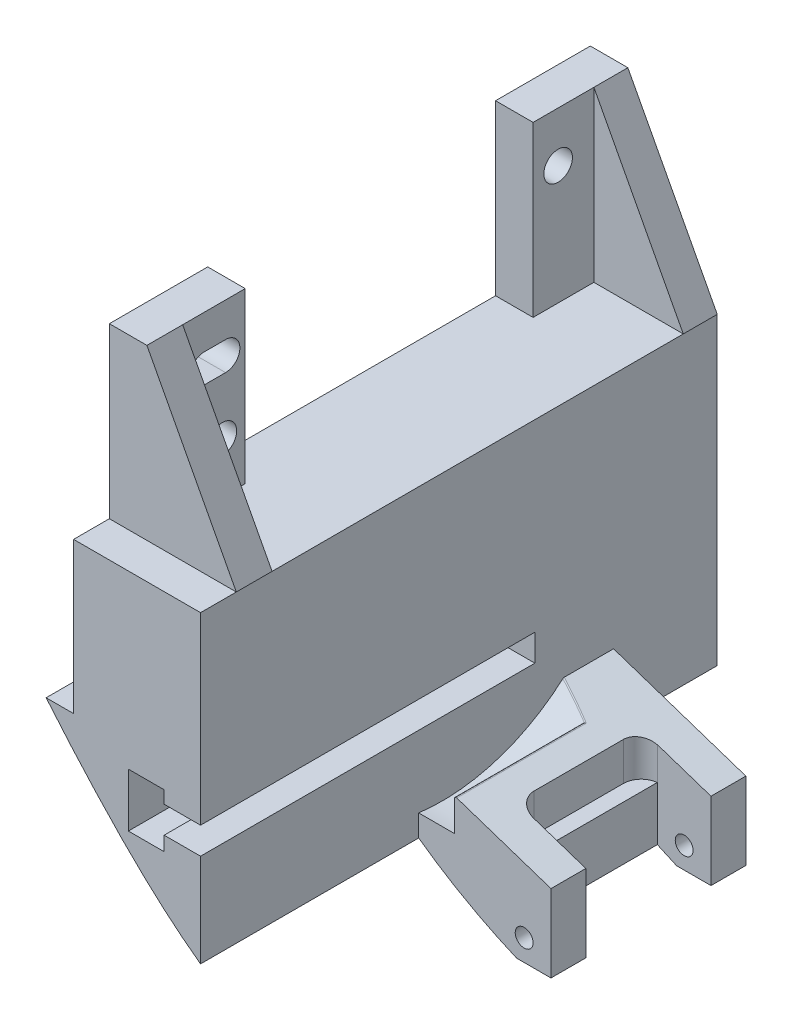
SolidWorks part; units mm, degrees
ref_plane "Front Plane" through (0, 0, 0) normal (0, 0, 1) x (1, 0, 0)
ref_plane "Top Plane" through (0, 0, 0) normal (0, 1, 0) x (1, 0, 0)
ref_plane "Right Plane" through (0, 0, 0) normal (1, 0, 0) x (0, 0, -1)
sketch "Sketch1" plane through (0, 0, 0) normal (0, 0, 1) x (1, 0, 0)
  line L0 (0, 0) -> (-802.64, 0) construction
  line L1 (-748.665, 44.1696) -> (-748.665, -74.6704)
  line L2 (-748.665, -30.2204) -> (-761.365, -6.2242)
  line L3 (-761.365, -6.2242) -> (-766.699, -6.2242)
  line L4 (-766.699, -6.2242) -> (-766.699, -51.6582)
  line L5 (-766.699, -51.6582) -> (-771.8965, -51.6582)
  line L6 (-748.665, -64.0024) -> (-729.869, -70.266)
  line L7 (-729.869, -70.266) -> (-729.869, -81.2664)
  line L8 (-729.869, -81.2664) -> (-737.2182, -81.2664)
  spline S0 degree 3 poles (0, 0) (-1.0237, 0.2656) (-4.9202, 1.2766) (-12.9449, 4.1039) (-25.4013, 8.4868) (-42.0665, 13.5118) (-62.8454, 18.7065) (-87.4855, 24.5937) (-115.6566, 31.0073) (-146.8786, 37.8673) (-180.6724, 44.9921) (-216.5548, 52.1802) (-254.0529, 59.2076) (-292.7123, 65.838) (-332.0988, 71.84) (-371.8025, 76.9957) (-411.4364, 81.107) (-450.6369, 83.9911) (-489.077, 85.531) (-526.5224, 85.442) (-562.7196, 83.818) (-597.4628, 80.7564) (-630.4517, 76.3148) (-661.4214, 70.7397) (-690.0483, 64.1559) (-716.031, 56.6856) (-739.0944, 48.4855) (-758.9977, 39.6811) (-775.5284, 30.474) (-788.4955, 21.0643) (-796.9293, 12.5202) (-800.9086, 6.2407) (-802.1089, 3.1045) (-802.4813, 1.6746) (-802.6246, 0.7789) (-802.6361, 0.1966) (-802.64, 0) knots 0 0 0 0 0.003802 0.014472 0.030564 0.051299 0.077028 0.107574 0.142399 0.180921 0.222525 0.266591 0.312515 0.35971 0.407632 0.455773 0.503669 0.550901 0.597096 0.641976 0.685512 0.727353 0.767354 0.805169 0.840471 0.872937 0.902335 0.928425 0.951113 0.970253 0.985871 0.993982 0.996753 0.997907 0.999293 1 1 1 1
  spline S1 degree 3 poles (-802.64, 0) (-802.6044, -0.5181) (-802.5144, -1.8305) (-801.9167, -4.3742) (-799.7349, -10.5214) (-793.9295, -20.2585) (-785.3431, -33.6018) (-775.1978, -47.9717) (-763.534, -61.6115) (-750.6842, -74.1505) (-734.4646, -83.2964) (-715.0378, -88.7141) (-692.4973, -92.3639) (-666.7697, -93.8876) (-638.0856, -93.4064) (-606.5863, -90.9175) (-572.4417, -86.5307) (-535.8367, -80.4015) (-496.9928, -72.7658) (-456.1802, -63.9255) (-413.7333, -54.2411) (-370.0617, -44.1324) (-325.6653, -34.0384) (-281.1348, -24.4182) (-237.1588, -15.6974) (-194.5105, -8.2549) (-154.0343, -2.3799) (-116.6158, 1.7567) (-83.1483, 4.1076) (-54.5227, 4.8332) (-31.6235, 4.0558) (-15.153, 2.4109) (-5.3471, 1.0064) (-1.061, 0.1997) (0, 0) knots 0 0 0 0 0.001821 0.004613 0.009135 0.024676 0.044153 0.064937 0.086321 0.107138 0.1276 0.150893 0.177565 0.207668 0.241222 0.278203 0.318526 0.362031 0.408465 0.457479 0.508614 0.561296 0.614835 0.668438 0.721214 0.772202 0.820393 0.864766 0.904324 0.938132 0.965242 0.98469 0.99621 1 1 1 1
  spline S2 degree 1 poles (-801.6423, 0.0685) (0.185, 0.9827) knots 0 0 1 1 construction
  spline S3 degree 3 poles (-801.6423, 0.0685) (-801.6237, -0.2032) (-801.5856, -0.7575) (-801.4767, -1.7745) (-801.2061, -3.0474) (-800.7523, -4.6051) (-799.6861, -7.6655) (-797.5851, -12.1121) (-794.186, -17.8214) (-789.4599, -25.3717) (-783.3821, -34.6366) (-775.6705, -45.5008) (-768.683, -54.0786) (-762.7345, -60.658) (-758.1103, -65.4458) (-753.2531, -69.943) (-746.3395, -75.3517) (-736.7143, -80.8312) (-724.2384, -85.2314) (-711.2485, -88.2163) (-698.134, -90.3911) (-684.9012, -91.7723) (-671.602, -92.498) (-653.8378, -92.7605) (-631.6341, -91.9649) (-605.061, -89.6531) (-578.5923, -86.3156) (-552.2299, -82.1851) (-517.21, -75.8642) (-473.6438, -66.8228) (-421.5579, -55.0352) (-369.5251, -42.9695) (-317.4245, -31.1532) (-265.1531, -20.0658) (-212.6314, -10.1632) (-159.8037, -1.9572) (-115.5013, 2.95) (-79.9088, 5.1973) (-53.1547, 5.839) (-30.8229, 5.0205) (-15.2792, 3.3879) (-6.4157, 2.1851) (-2.0125, 1.3963) (0.185, 0.9827) knots 0 0 0 0 0.000977 0.001953 0.003906 0.005859 0.007812 0.015625 0.023437 0.03125 0.046875 0.0625 0.078125 0.085937 0.09375 0.101562 0.109375 0.125 0.140625 0.15625 0.171875 0.1875 0.203125 0.21875 0.25 0.28125 0.3125 0.34375 0.375 0.4375 0.5 0.5625 0.625 0.6875 0.75 0.8125 0.875 0.90625 0.9375 0.96875 0.984375 0.992187 1 1 1 1
  point P6 (-748.665, -30.2204)
  dimension "D2" = 802.64
  dimension "D3" = 44.45
  dimension "D4" = 18.034
  dimension "D5" = 5.334
  dimension "D6" = 117.89
  dimension "D7" = 1
  dimension "D8" = 108.43
  dimension "D9" = 18.796
  dimension "D10" = 10.668
  dimension "D11" = 53.975
extrude "Boss-Extrude1" add sketch "Sketch1" along normal blind 73.406 contours L5 S1 L1 L2 L3 L4 | L1 S1 L8 L7 L6
sketch "Sketch2" plane through (-748.665, 0, 0) normal (1, 0, 0) x (0, 0, -1)
  line L0 (-73.406, -30.2204) -> (0, -30.2204) construction
  line L1 (-73.406, -6.2242) -> (-68.326, -6.2242)
  line L2 (-73.406, -6.2242) -> (-73.406, -30.2204)
  line L3 (-73.406, -30.2204) -> (-68.326, -30.2204)
  line L4 (-68.326, -6.2242) -> (-68.326, -30.2204)
  line L5 (-73.406, -6.2242) -> (0, -6.2242) construction
  line L6 (-54.356, -6.2242) -> (-13.462, -6.2242)
  line L7 (-54.356, -6.2242) -> (-54.356, -30.2204)
  line L8 (-54.356, -30.2204) -> (-13.462, -30.2204)
  line L9 (-13.462, -6.2242) -> (-13.462, -30.2204)
  dimension "D1" = 5.08
  dimension "D2" = 13.97
  dimension "D3" = 40.894
extrude "Cut-Extrude1" cut sketch "Sketch2" against normal through all
sketch "Sketch3" plane through (-748.665, 0, 0) normal (1, 0, 0) x (0, 0, -1)
  line L0 (-68.326, -6.2242) -> (-54.356, -6.2242) construction
  line L1 (-63.246, -6.2242) -> (-4.826, -6.2242)
  line L2 (-63.246, -6.2242) -> (-63.246, -30.2204)
  line L3 (-63.246, -30.2204) -> (-4.826, -30.2204)
  line L4 (-4.826, -6.2242) -> (-4.826, -30.2204)
  line L5 (-13.462, -30.2204) -> (0, -30.2204) construction
  line L6 (-68.326, -6.2242) -> (-68.326, -30.2204) construction
  point P10 (-63.246, -18.2223)
  dimension "D1" = 5.08
  dimension "D2" = 58.42
extrude "Cut-Extrude2" cut sketch "Sketch3" against normal up to vertex (12.7 mm away) up to point (-761.365, -6.2242, 13.462)
sketch "Sketch4" plane through (-761.365, 0, 0) normal (1, 0, 0) x (0, 0, -1)
  line L0 (-60.198, -13.1338) -> (-57.15, -13.1338) construction
  line L3 (-10.668, -33.8067) -> (-7.62, -33.8067) construction
  line L6 (-60.198, -11.1018) -> (-57.15, -11.1018)
  line L7 (-63.246, -30.2204) -> (-54.356, -30.2204) construction
  line L8 (-4.826, -30.2204) -> (-4.826, -6.2242) construction
  line L9 (-13.462, -6.2242) -> (-4.826, -6.2242) construction
  line L10 (-4.826, -6.2242) -> (-4.826, -30.2204) construction
  line L12 (-60.198, -15.1658) -> (-57.15, -15.1658)
  line L13 (-54.356, -6.2242) -> (-63.246, -6.2242) construction
  line L14 (-63.246, -30.2204) -> (-63.246, -6.2242) construction
  line L15 (-10.668, -31.7747) -> (-7.62, -31.7747)
  line L16 (-10.668, -35.8387) -> (-7.62, -35.8387)
  circle A0 centre (-57.6105, -23.1084) radius 2.032
  circle A1 centre (-9.906, -13.3362) radius 2.032
  arc A6 (-60.198, -11.1018) -> (-60.198, -15.1658) centre (-60.198, -13.1338) ccw
  arc A7 (-57.15, -15.1658) -> (-57.15, -11.1018) centre (-57.15, -13.1338) ccw
  arc A8 (-10.668, -31.7747) -> (-10.668, -35.8387) centre (-10.668, -33.8067) ccw
  arc A9 (-7.62, -35.8387) -> (-7.62, -31.7747) centre (-7.62, -33.8067) ccw
  point P6 (-58.674, -13.1338)
  point P13 (-9.144, -33.8067)
  dimension "D3" = 4.064
  dimension "D4" = 4.064
  dimension "D5" = 5.08
  dimension "D6" = 7.112
  dimension "D8" = 4.064
  dimension "D14" = 4.318
  dimension "D10" = 2.032
  dimension "D2" = 7.112
  dimension "D7" = 3.048
  dimension "D9" = 3.048
  dimension "D11" = 6.9096
  dimension "D12" = 4.572
  dimension "D13" = 5.6355
extrude "Cut-Extrude3" cut sketch "Sketch4" against normal through all
sketch "Sketch5" plane through (-729.869, 0, 0) normal (1, 0, 0) x (0, 0, -1)
  line L0 (-73.406, -81.2664) -> (0, -81.2664) construction
  line L1 (-73.406, -64.0024) -> (-42.418, -64.0024)
  line L2 (-73.406, -64.0024) -> (-73.406, -81.2664)
  line L3 (-73.406, -81.2664) -> (-42.418, -81.2664)
  line L4 (-42.418, -64.0024) -> (-42.418, -81.2664)
  line L5 (-73.406, -64.0024) -> (0, -64.0024) construction
  line L6 (-14.732, -64.0024) -> (0, -64.0024)
  line L7 (-14.732, -64.0024) -> (-14.732, -81.2664)
  line L8 (-14.732, -81.2664) -> (0, -81.2664)
  line L9 (0, -64.0024) -> (0, -81.2664)
  dimension "D1" = 30.988
  dimension "D2" = 14.732
extrude "Cut-Extrude4" cut sketch "Sketch5" against normal up to vertex (18.796 mm away)
sketch "Sketch6" plane through (0, 0, 73.406) normal (0, 0, 1) x (1, 0, 0)
  line L10 (-748.665, 44.1696) -> (-748.665, -74.6704) construction
  line L11 (-748.665, -56.3744) -> (-748.665, -60.1844)
  line L12 (-748.665, -60.1844) -> (-753.8364, -60.1844)
  line L13 (-753.8364, -60.1844) -> (-753.8364, -62.2164)
  line L14 (-753.8364, -62.2164) -> (-758.9164, -62.2164)
  line L15 (-758.9164, -62.2164) -> (-758.9164, -54.5964)
  line L16 (-758.9164, -54.5964) -> (-753.8364, -54.5964)
  line L17 (-753.8364, -54.5964) -> (-753.8364, -56.3744)
  line L18 (-753.8364, -56.3744) -> (-748.665, -56.3744)
  line L19 (-729.869, -81.2664) -> (-737.2182, -81.2664) construction
  dimension "D7" = 7.62
  dimension "D8" = 5.08
  dimension "D9" = 5.1714
  dimension "D10" = 3.81
  dimension "D11" = 2.032
  dimension "D12" = 19.05
extrude "Cut-Extrude5" cut sketch "Sketch6" against normal blind 47.498
sketch "Sketch7" plane through (0, -81.2664, 0) normal (0, -1, 0) x (1, 0, 0)
  line L0 (-729.869, 42.418) -> (-729.869, 14.732) construction
  line L1 (-729.869, 37.465) -> (-737.489, 37.465)
  line L2 (-729.869, 37.465) -> (-729.869, 19.685)
  line L3 (-729.869, 19.685) -> (-737.489, 19.685)
  line L4 (-737.489, 37.465) -> (-737.489, 19.685)
  line L5 (-734.751, 42.418) -> (-729.869, 42.418) construction
  line L6 (-734.751, 14.732) -> (-729.869, 14.732) construction
  dimension "D1" = 7.62
  dimension "D2" = 17.78
  dimension "D3" = 4.953
  dimension "D4" = 4.953
extrude "Cut-Extrude6" cut sketch "Sketch7" against normal blind 22.098
sketch "Sketch8" plane through (0, -30.2204, 0) normal (0, 1, 0) x (1, 0, 0)
  line L1 (-729.869, -37.465) -> (-737.235, -37.465)
  line L2 (-729.869, -37.465) -> (-729.869, -19.685)
  line L3 (-729.869, -19.685) -> (-737.235, -19.685)
  line L4 (-739.775, -34.925) -> (-739.775, -22.225)
  arc A0 (-737.235, -19.685) -> (-739.775, -22.225) centre (-737.235, -22.225) ccw
  arc A1 (-739.775, -34.925) -> (-737.235, -37.465) centre (-737.235, -34.925) ccw
  dimension "D3" = 2.54
  dimension "D1" = 17.78
  dimension "D2" = 9.906
extrude "Cut-Extrude7" cut sketch "Sketch8" against normal blind 42.164
sketch "Sketch9" plane through (0, 0, 42.418) normal (0, 0, 1) x (1, 0, 0)
  line L0 (-729.869, -81.2664) -> (-729.869, -70.266) construction
  line L1 (-734.751, -81.2664) -> (-729.869, -81.2664) construction
  circle A0 centre (-733.679, -78.2184) radius 1.27
  dimension "D1" = 2.54
  dimension "D2" = 3.81
  dimension "D3" = 3.048
extrude "Cut-Extrude8" cut sketch "Sketch9" against normal through all
sketch "Sketch12" plane through (-748.665, 0, 0) normal (1, 0, 0) x (0, 0, -1)
  line L0 (-42.418, -64.0024) -> (-21.844, -64.0024)
  line L1 (-42.418, -64.0024) -> (-14.732, -64.0024) construction
  line L2 (-42.418, -64.0024) -> (-42.418, -70.3524)
  line L3 (-42.418, -70.266) -> (-42.418, -64.0024) construction
  arc A0 (-42.418, -70.3524) -> (-21.844, -64.0024) centre (-39.0807, -44.6603) ccw
  dimension "D3" = 25.908
  dimension "D1" = 20.574
  dimension "D2" = 6.35
extrude "Cut-Extrude9" cut sketch "Sketch12" along normal blind 5.08
fillet "Fillet1" radius 0.254 2 edges at (-746.0422, -64.8765, 22.878) (-743.585, -65.6953, 33.1871)
